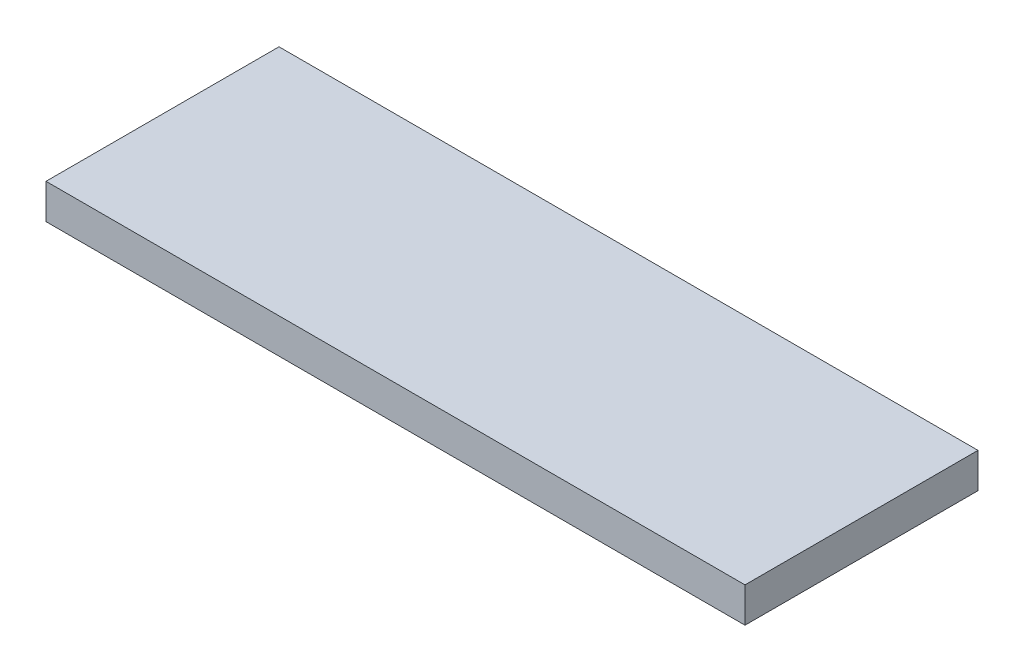
SolidWorks part; units mm, degrees
ref_plane "Front Plane" through (0, 0, 0) normal (0, 0, 1) x (1, 0, 0)
ref_plane "Top Plane" through (0, 0, 0) normal (0, 1, 0) x (1, 0, 0)
ref_plane "Right Plane" through (0, 0, 0) normal (1, 0, 0) x (0, 0, -1)
sketch "Sketch1" plane through (0, 0, 0) normal (0, 1, 0) x (1, 0, 0)
  line L1 (-30, 10) -> (30, 10)
  line L2 (-30, 10) -> (-30, -10)
  line L3 (-30, -10) -> (30, -10)
  line L4 (30, 10) -> (30, -10)
  line L5 (-30, 10) -> (30, -10) construction
  line L6 (-30, -10) -> (30, 10) construction
  point P0 (0, 0)
  dimension "D1" = 20
  dimension "D2" = 60
extrude "Boss-Extrude1" add sketch "Sketch1" along normal blind 3
